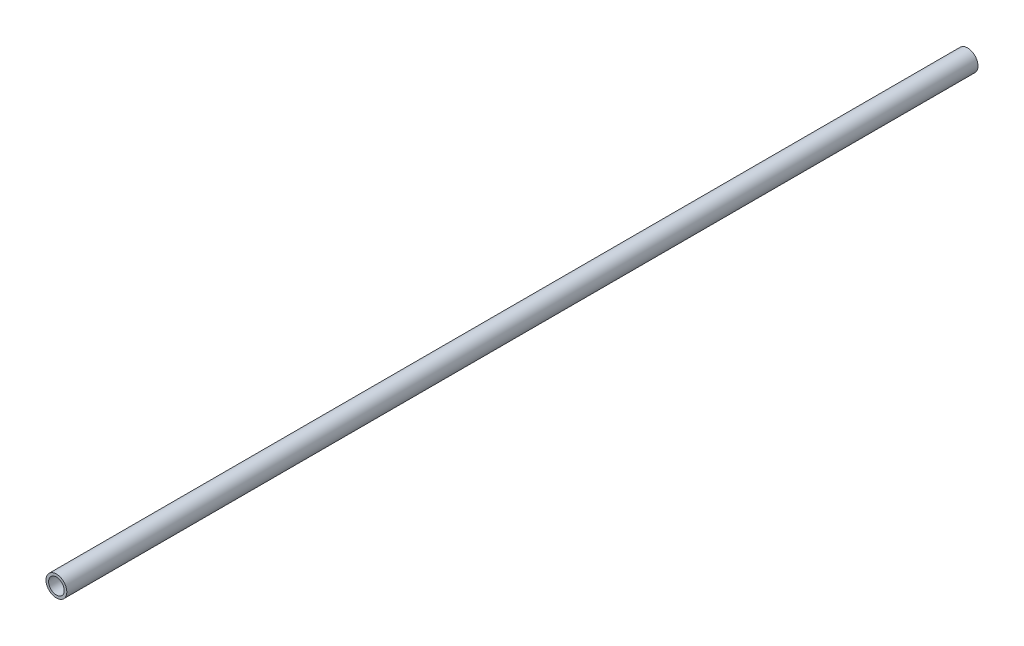
SolidWorks part; units mm, degrees
ref_plane "Front Plane" through (0, 0, 0) normal (0, 0, 1) x (1, 0, 0)
ref_plane "Top Plane" through (0, 0, 0) normal (0, 1, 0) x (1, 0, 0)
ref_plane "Right Plane" through (0, 0, 0) normal (1, 0, 0) x (0, 0, -1)
sketch "Sketch1" plane through (0, 0, 0) normal (0, 0, 1) x (1, 0, 0)
  circle A0 centre (0, 0) radius 4
  circle A1 centre (0, 0) radius 3
extrude "Boss-Extrude1" add sketch "Sketch1" along normal blind 350
